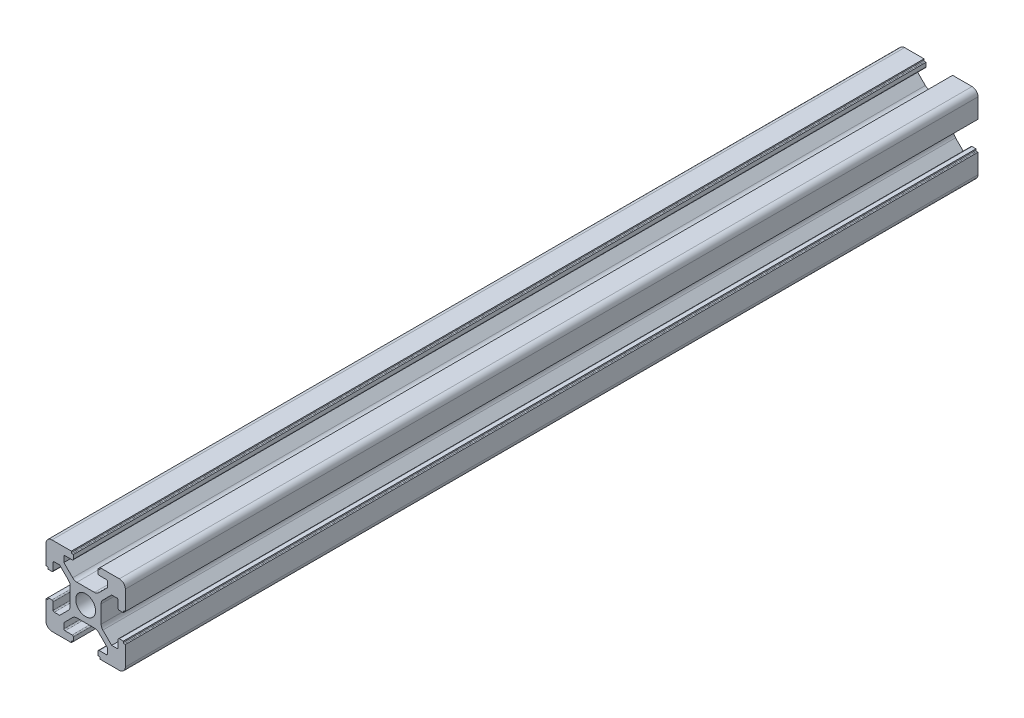
SolidWorks part; units mm, degrees
ref_plane "前视基准面" through (0, 0, 0) normal (0, 0, 1) x (1, 0, 0)
ref_plane "上视基准面" through (0, 0, 0) normal (0, 1, 0) x (1, 0, 0)
ref_plane "右视基准面" through (0, 0, 0) normal (1, 0, 0) x (0, 0, -1)
sketch "草图1" plane through (0, 0, 0) normal (0, 0, 1) x (1, 0, 0)
  line L0 (4.216, 3.2442) -> (6.4367, 5.4649)
  line L1 (6.4367, 5.4649) -> (7.7767, 5.4649)
  line L2 (8.0767, 5.1649) -> (8.0767, 3.3649)
  line L3 (8.3767, 3.0649) -> (9.3767, 3.0649)
  line L4 (9.3767, 3.0649) -> (9.3767, 3.3649)
  line L5 (9.5767, 3.5649) -> (9.8767, 3.5649)
  line L6 (9.8767, 3.5649) -> (9.8767, 8.4649)
  line L7 (8.3767, 9.9649) -> (3.4767, 9.9649)
  line L8 (3.4767, 9.9649) -> (3.4767, 9.6649)
  line L9 (3.2767, 9.4649) -> (2.9767, 9.4649)
  line L10 (2.9767, 9.4649) -> (2.9767, 8.4649)
  line L11 (3.2767, 8.1649) -> (5.0767, 8.1649)
  line L12 (5.3767, 7.8649) -> (5.3767, 6.5249)
  line L13 (5.3767, 6.5249) -> (3.156, 4.3042)
  line L14 (2.0953, 3.8649) -> (-2.342, 3.8649)
  line L15 (-3.4027, 4.3042) -> (-5.6233, 6.5249)
  line L16 (-5.6233, 6.5249) -> (-5.6233, 7.8649)
  line L17 (-5.3233, 8.1649) -> (-3.5233, 8.1649)
  line L18 (-3.2233, 8.4649) -> (-3.2233, 9.4649)
  line L19 (-3.2233, 9.4649) -> (-3.5233, 9.4649)
  line L20 (-3.7233, 9.6649) -> (-3.7233, 9.9649)
  line L21 (-3.7233, 9.9649) -> (-8.6233, 9.9649)
  line L22 (-10.1233, 8.4649) -> (-10.1233, 3.5649)
  line L23 (-10.1233, 3.5649) -> (-9.8233, 3.5649)
  line L24 (-9.6233, 3.3649) -> (-9.6233, 3.0649)
  line L25 (-9.6233, 3.0649) -> (-8.6233, 3.0649)
  line L26 (-8.3233, 3.3649) -> (-8.3233, 5.1649)
  line L27 (-8.0233, 5.4649) -> (-6.6833, 5.4649)
  line L28 (-6.6833, 5.4649) -> (-4.4627, 3.2442)
  line L29 (-4.0233, 2.1836) -> (-4.0233, -2.2538)
  line L30 (-4.4627, -3.3144) -> (-6.6833, -5.5351)
  line L31 (-6.6833, -5.5351) -> (-8.0233, -5.5351)
  line L32 (-8.3233, -5.2351) -> (-8.3233, -3.4351)
  line L33 (-8.6233, -3.1351) -> (-9.6233, -3.1351)
  line L34 (-9.6233, -3.1351) -> (-9.6233, -3.4351)
  line L35 (-9.8233, -3.6351) -> (-10.1233, -3.6351)
  line L36 (-10.1233, -3.6351) -> (-10.1233, -8.5351)
  line L37 (-8.6233, -10.0351) -> (-3.7233, -10.0351)
  line L38 (-3.7233, -10.0351) -> (-3.7233, -9.7351)
  line L39 (-3.5233, -9.5351) -> (-3.2233, -9.5351)
  line L40 (-3.2233, -9.5351) -> (-3.2233, -8.5351)
  line L41 (-3.5233, -8.2351) -> (-5.3233, -8.2351)
  line L42 (-5.6233, -7.9351) -> (-5.6233, -6.5951)
  line L43 (-5.6233, -6.5951) -> (-3.4027, -4.3744)
  line L44 (-2.342, -3.9351) -> (2.0953, -3.9351)
  line L45 (3.156, -4.3744) -> (5.3767, -6.5951)
  line L46 (5.3767, -6.5951) -> (5.3767, -7.9351)
  line L47 (5.0767, -8.2351) -> (3.2767, -8.2351)
  line L48 (2.9767, -8.5351) -> (2.9767, -9.5351)
  line L49 (2.9767, -9.5351) -> (3.2767, -9.5351)
  line L50 (3.4767, -9.7351) -> (3.4767, -10.0351)
  line L51 (3.4767, -10.0351) -> (8.3767, -10.0351)
  line L52 (9.8767, -8.5351) -> (9.8767, -3.6351)
  line L53 (9.8767, -3.6351) -> (9.5767, -3.6351)
  line L54 (9.3767, -3.4351) -> (9.3767, -3.1351)
  line L55 (9.3767, -3.1351) -> (8.3767, -3.1351)
  line L56 (8.0767, -3.4351) -> (8.0767, -5.2351)
  line L57 (7.7767, -5.5351) -> (6.4367, -5.5351)
  line L58 (6.4367, -5.5351) -> (4.216, -3.3144)
  line L59 (3.7767, -2.2538) -> (3.7767, 2.1836)
  circle A0 centre (-0.1233, -0.0351) radius 2.5
  arc A1 (8.0767, 5.1649) -> (7.7767, 5.4649) centre (7.7767, 5.1649) ccw
  arc A2 (8.0767, 3.3649) -> (8.3767, 3.0649) centre (8.3767, 3.3649) ccw
  arc A3 (9.5767, 3.5649) -> (9.3767, 3.3649) centre (9.5767, 3.3649) ccw
  arc A4 (9.8767, 8.4649) -> (8.3767, 9.9649) centre (8.3767, 8.4649) ccw
  arc A5 (3.2767, 9.4649) -> (3.4767, 9.6649) centre (3.2767, 9.6649) ccw
  arc A6 (2.9767, 8.4649) -> (3.2767, 8.1649) centre (3.2767, 8.4649) ccw
  arc A7 (5.3767, 7.8649) -> (5.0767, 8.1649) centre (5.0767, 7.8649) ccw
  arc A8 (2.0953, 3.8649) -> (3.156, 4.3042) centre (2.0953, 5.3649) ccw
  arc A9 (-3.4027, 4.3042) -> (-2.342, 3.8649) centre (-2.342, 5.3649) ccw
  arc A10 (-5.3233, 8.1649) -> (-5.6233, 7.8649) centre (-5.3233, 7.8649) ccw
  arc A11 (-3.5233, 8.1649) -> (-3.2233, 8.4649) centre (-3.5233, 8.4649) ccw
  arc A12 (-3.7233, 9.6649) -> (-3.5233, 9.4649) centre (-3.5233, 9.6649) ccw
  arc A13 (-8.6233, 9.9649) -> (-10.1233, 8.4649) centre (-8.6233, 8.4649) ccw
  arc A14 (-9.6233, 3.3649) -> (-9.8233, 3.5649) centre (-9.8233, 3.3649) ccw
  arc A15 (-8.6233, 3.0649) -> (-8.3233, 3.3649) centre (-8.6233, 3.3649) ccw
  arc A16 (-8.0233, 5.4649) -> (-8.3233, 5.1649) centre (-8.0233, 5.1649) ccw
  arc A17 (-4.0233, 2.1836) -> (-4.4627, 3.2442) centre (-5.5233, 2.1836) ccw
  arc A18 (-4.4627, -3.3144) -> (-4.0233, -2.2538) centre (-5.5233, -2.2538) ccw
  arc A19 (-8.3233, -5.2351) -> (-8.0233, -5.5351) centre (-8.0233, -5.2351) ccw
  arc A20 (-8.3233, -3.4351) -> (-8.6233, -3.1351) centre (-8.6233, -3.4351) ccw
  arc A21 (-9.8233, -3.6351) -> (-9.6233, -3.4351) centre (-9.8233, -3.4351) ccw
  arc A22 (-10.1233, -8.5351) -> (-8.6233, -10.0351) centre (-8.6233, -8.5351) ccw
  arc A23 (-3.5233, -9.5351) -> (-3.7233, -9.7351) centre (-3.5233, -9.7351) ccw
  arc A24 (-3.2233, -8.5351) -> (-3.5233, -8.2351) centre (-3.5233, -8.5351) ccw
  arc A25 (-5.6233, -7.9351) -> (-5.3233, -8.2351) centre (-5.3233, -7.9351) ccw
  arc A26 (-2.342, -3.9351) -> (-3.4027, -4.3744) centre (-2.342, -5.4351) ccw
  arc A27 (3.156, -4.3744) -> (2.0953, -3.9351) centre (2.0953, -5.4351) ccw
  arc A28 (5.0767, -8.2351) -> (5.3767, -7.9351) centre (5.0767, -7.9351) ccw
  arc A29 (3.2767, -8.2351) -> (2.9767, -8.5351) centre (3.2767, -8.5351) ccw
  arc A30 (3.4767, -9.7351) -> (3.2767, -9.5351) centre (3.2767, -9.7351) ccw
  arc A31 (8.3767, -10.0351) -> (9.8767, -8.5351) centre (8.3767, -8.5351) ccw
  arc A32 (9.3767, -3.4351) -> (9.5767, -3.6351) centre (9.5767, -3.4351) ccw
  arc A33 (8.3767, -3.1351) -> (8.0767, -3.4351) centre (8.3767, -3.4351) ccw
  arc A34 (7.7767, -5.5351) -> (8.0767, -5.2351) centre (7.7767, -5.2351) ccw
  arc A35 (3.7767, -2.2538) -> (4.216, -3.3144) centre (5.2767, -2.2538) ccw
  arc A36 (4.216, 3.2442) -> (3.7767, 2.1836) centre (5.2767, 2.1836) ccw
extrude "凸台-拉伸1" add sketch "草图1" along normal blind 215
